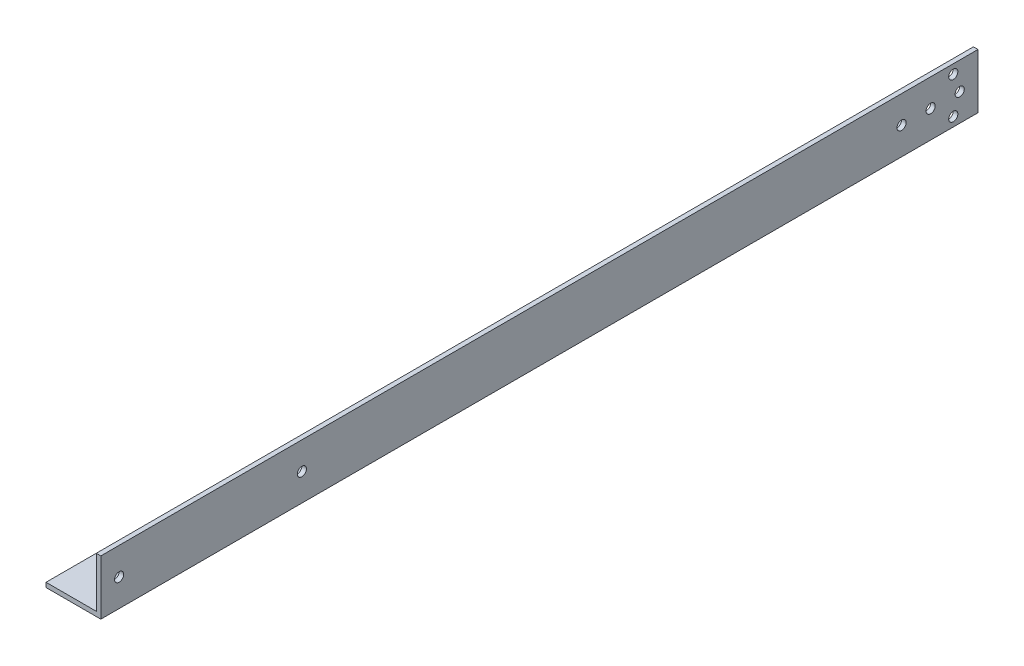
SolidWorks part; units mm, degrees
material "6061 Alloy"
ref_plane "Front Plane" through (0, 0, 0) normal (0, 0, 1) x (1, 0, 0)
ref_plane "Top Plane" through (0, 0, 0) normal (0, 1, 0) x (1, 0, 0)
ref_plane "Right Plane" through (0, 0, 0) normal (1, 0, 0) x (0, 0, -1)
sketch "Sketch1" plane through (0, 0, 0) normal (0, 0, 1) x (1, 0, 0)
  line L0 (0, 0) -> (0, 19.05)
  line L1 (0, 19.05) -> (-1.5875, 19.05)
  line L2 (-1.5875, 19.05) -> (-1.5875, 1.5875)
  line L3 (-1.5875, 1.5875) -> (-19.05, 1.5875)
  line L4 (-19.05, 1.5875) -> (-19.05, 0)
  line L5 (-19.05, 0) -> (0, 0)
  dimension "width" = 19.05
  dimension "thickness" = 1.5875
extrude "Extrude1" add sketch "Sketch1" along normal blind 304.8
sketch "Sketch2" plane through (0, 0, 0) normal (1, 0, 0) x (0, 0, -1)
  line L0 (-304.8, 0) -> (0, 0) construction
  line L2 (-304.8, 0) -> (-304.8, 19.05) construction
  circle A0 centre (-298.45, 9.525) radius 1.5875
  circle A1 centre (-234.95, 9.525) radius 1.5875
  dimension "D1" = 63.5
  dimension "D2" = 6.35
  dimension "hole_dia" = 3.175
  dimension "D3" = 9.525
extrude "Extrude2" cut sketch "Sketch2" against normal up to surface (1.5875 mm away) up to face at (-1.5875, 10.3188, 152.4)
sketch "Sketch3" plane through (0, 0, 0) normal (1, 0, 0) x (0, 0, -1)
  line L0 (-304.8, 0) -> (0, 0) construction
  line L2 (0, 0) -> (0, 19.05) construction
  circle A0 centre (-16.4528, 9.525) radius 10.1028
  circle A1 centre (-26.5556, 9.525) radius 1.5875
  circle A2 centre (-8.5951, 15.875) radius 1.5875
  circle A3 centre (-8.5951, 3.175) radius 1.5875
  circle A4 centre (-16.4528, 9.525) radius 1.5875
  dimension "D1" = 9.525
  dimension "D2" = 19.05
  dimension "D3" = 19.05
  dimension "D4" = 12.7
  dimension "D5" = 16.4528
  dimension "D6" = 20.2056
extrude "Cut-Extrude3" cut sketch "Sketch3" against normal through all contours A4 | A1
sketch "Sketch6" plane through (0, 0, 0) normal (1, 0, 0) x (0, 0, -1)
  circle A0 centre (-16.4528, 9.525) radius 10.1028
  circle A1 centre (-8.5951, 15.875) radius 1.5875
  circle A2 centre (-8.5951, 3.175) radius 1.5875
  circle A3 centre (-26.5556, 9.525) radius 1.5875 construction
  circle A4 centre (-6.35, 9.525) radius 1.5875
  circle A5 centre (-16.4528, 9.525) radius 1.5875 construction
  dimension "D1" = 19.05
  dimension "D2" = 19.05
  dimension "D3" = 6.35
  dimension "D4" = 12.7
extrude "Cut-Extrude5" cut sketch "Sketch6" against normal through all contours A1 | A2 | A4
sketch "Sketch7" plane through (0, 1.5875, 0) normal (0, 1, 0) x (1, 0, 0)
  line L0 (-19.05, -304.8) -> (-19.05, 0) construction
  line L1 (-1.5875, 0) -> (-19.05, 0)
  line L2 (-1.5875, 0) -> (-1.5875, -11.7701)
  line L3 (-1.5875, -11.7701) -> (-19.05, -11.7701)
  line L4 (-19.05, 0) -> (-19.05, -11.7701)
  line L6 (-0.5475, -8.5951) -> (-19.05, -8.5951)
  dimension "D1" = 3.175
extrude "Cut-Extrude6" cut sketch "Sketch7" against normal through all contours L4 L3 L2 L1
equation "\"D3@Sketch2\" = \"width\" / 2"
equation "\"D5@Sketch3\" = \"D6@Sketch3\" / 2 + 0.25"
